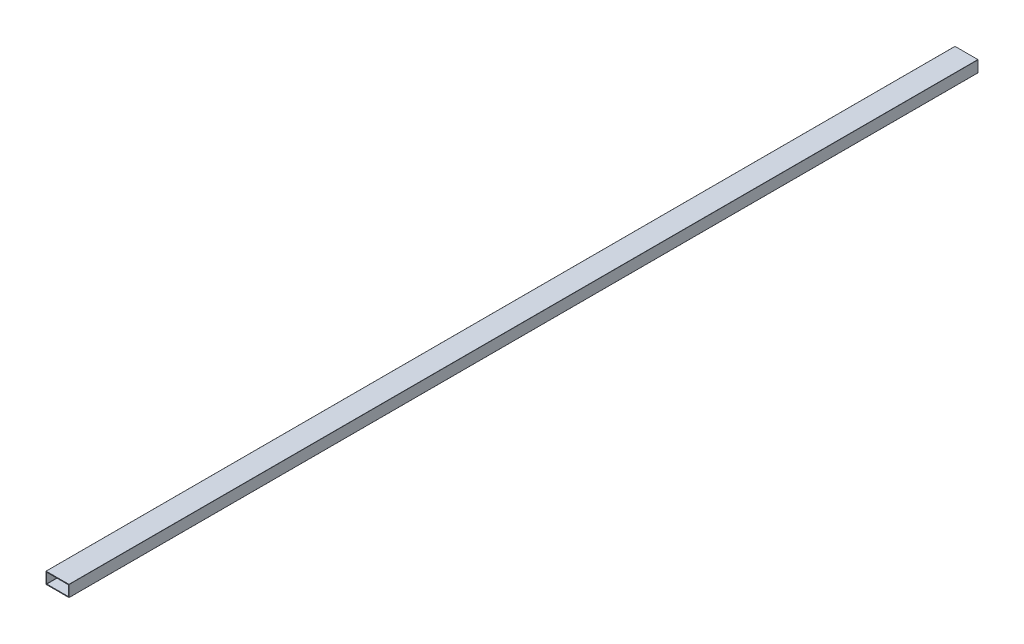
SolidWorks part; units mm, degrees
material "AISI 1035 Acero (SS)"
ref_plane "Alzado" through (0, 0, 0) normal (0, 0, 1) x (1, 0, 0)
ref_plane "Planta" through (0, 0, 0) normal (0, 1, 0) x (1, 0, 0)
ref_plane "Vista lateral" through (0, 0, 0) normal (1, 0, 0) x (0, 0, -1)
sketch "Croquis1" plane through (0, 0, 0) normal (0, 0, 1) x (1, 0, 0)
  line L0 (-71.65, -33.55) -> (-71.65, 33.55)
  line L1 (-76.2, -38.1) -> (76.2, -38.1)
  line L2 (-76.2, -38.1) -> (-76.2, 38.1)
  line L3 (-76.2, 38.1) -> (76.2, 38.1)
  line L4 (76.2, -38.1) -> (76.2, 38.1)
  line L5 (-76.2, -38.1) -> (76.2, 38.1) construction
  line L6 (-76.2, 38.1) -> (76.2, -38.1) construction
  line L7 (-71.65, 33.55) -> (71.65, 33.55)
  line L8 (71.65, -33.55) -> (71.65, 33.55)
  line L9 (-71.65, -33.55) -> (71.65, -33.55)
  point P0 (0, 0)
  dimension "D1" = 76.2
  dimension "D2" = 152.4
  dimension "D3" = 4.55
extrude "Saliente-Extruir1" add sketch "Croquis1" against normal blind 6000
fillet "Redondeo1" radius 1 8 edges at (-71.65, 33.55, -3000) (71.65, 33.55, -3000) (71.65, -33.55, -3000) (-76.2, -38.1, -3000) (-76.2, 38.1, -3000) (-71.65, -33.55, -3000) (76.2, -38.1, -3000) (76.2, 38.1, -3000)
